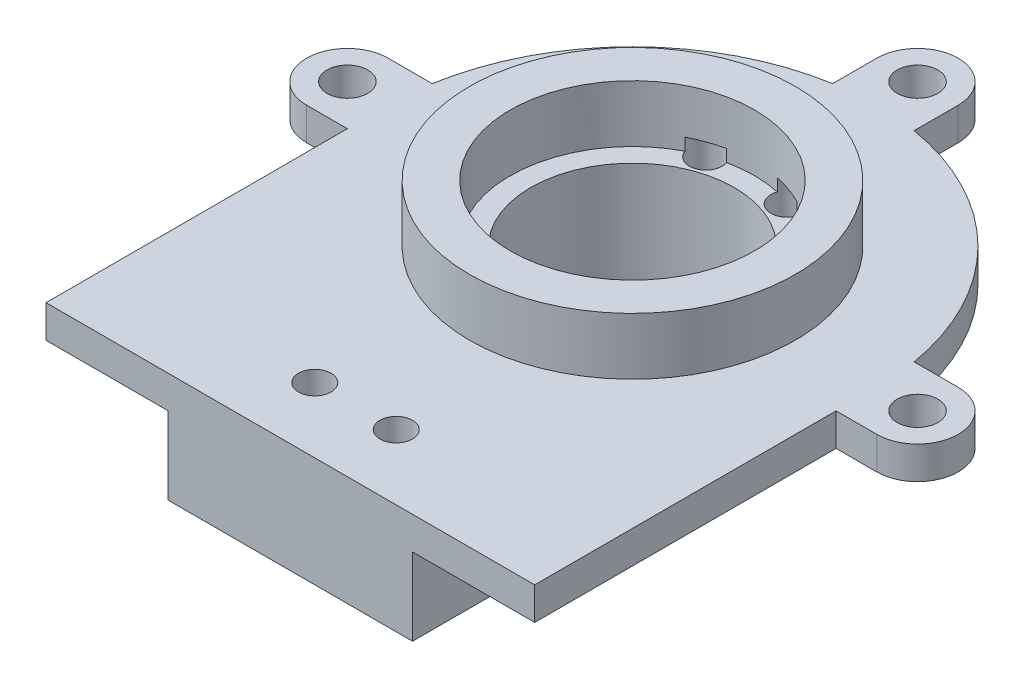
SolidWorks part; units mm, degrees
ref_plane "Спереди" through (0, 0, 0) normal (0, 0, 1) x (1, 0, 0)
ref_plane "Сверху" through (0, 0, 0) normal (0, 1, 0) x (1, 0, 0)
ref_plane "Справа" through (0, 0, 0) normal (1, 0, 0) x (0, 0, -1)
sketch "Эскиз1" plane through (0, 0, 0) normal (0, 1, 0) x (1, 0, 0)
  circle A0 centre (0, 0) radius 20
  circle A1 centre (0, 0) radius 15
  dimension "D1" = 40
  dimension "D2" = 30
extrude "Бобышка-Вытянуть1" add sketch "Эскиз1" along normal blind 7
sketch "Эскиз2" plane through (0, 0, 0) normal (0, -1, 0) x (1, 0, 0)
  circle A0 centre (0, 0) radius 70
  circle A1 centre (0, 0) radius 12.5
  dimension "D1" = 140
  dimension "D2" = 25
extrude "Бобышка-Вытянуть2" add sketch "Эскиз2" along normal blind 4
sketch "Эскиз3" plane through (0, -4, 0) normal (0, -1, 0) x (1, 0, 0)
  line L0 (10, -6.7) -> (10, 26.7) construction
  line L1 (15, -22) -> (-15, -22)
  line L2 (15, -22) -> (15, 42)
  line L3 (15, 42) -> (-15, 42)
  line L4 (-15, -22) -> (-15, 42)
  line L5 (-10, 26.7) -> (-10, -6.7) construction
  line L6 (-3.6083, -17) -> (3.6083, -17) construction
  line L7 (3.6083, 37) -> (-3.6083, 37) construction
  circle A0 centre (-5, 34) radius 2
  circle A1 centre (5, 34) radius 2
  circle A2 centre (-5, -14) radius 2
  circle A3 centre (5, -14) radius 2
  circle A4 centre (0, 0) radius 12.5
  dimension "D5" = 25
  dimension "D1" = 5
  dimension "D2" = 5
  dimension "D3" = 5
  dimension "D4" = 5
extrude "Бобышка-Вытянуть3" add sketch "Эскиз3" along normal blind 9.5
sketch "Эскиз4" plane through (0, 0, 0) normal (0, 1, 0) x (1, 0, 0)
  line L0 (-1000, 0) -> (49000, 0) construction
  line L1 (-30, 0) -> (-30, -42)
  line L2 (-30, -42) -> (30, -42)
  line L3 (30, -42) -> (30, 0)
  arc A0 (30, 0) -> (-30, 0) centre (0, 0) ccw
  circle A1 centre (0, 0) radius 81.1685
  dimension "D1" = 60
  dimension "D2" = 60
  dimension "D3" = 42
extrude "Вырез-Вытянуть1" cut sketch "Эскиз4" against normal blind 9.5
sketch "Эскиз6" plane through (0, -13.5, 0) normal (0, -1, 0) x (1, 0, 0)
  circle A0 centre (-5, 34) radius 2
  circle A1 centre (5, 34) radius 2
  circle A2 centre (-5, -14) radius 2
  circle A3 centre (5, -14) radius 2
extrude "Вырез-Вытянуть2" cut sketch "Эскиз6" against normal blind 15
sketch "Эскиз7" plane through (0, 0, 0) normal (0, 1, 0) x (1, 0, 0)
  line L0 (-1000, 0) -> (49000, 0) construction
  line L1 (0, -1000) -> (0, 49000) construction
  line L2 (-35, 5) -> (-27, 5)
  line L3 (-27, 5) -> (-27, -5)
  line L4 (-27, -5) -> (-35, -5)
  line L5 (-5, 35) -> (-5, 27)
  line L6 (-5, 27) -> (5, 27)
  line L7 (5, 27) -> (5, 35)
  line L8 (35, 5) -> (27, 5)
  line L9 (27, 5) -> (27, -5)
  line L10 (27, -5) -> (35, -5)
  circle A0 centre (-35, 0) radius 2.5
  circle A1 centre (35, 0) radius 2.5
  circle A2 centre (0, 35) radius 2.5
  arc A3 (-35, 5) -> (-35, -5) centre (-35, 0) ccw
  arc A5 (5, 35) -> (-5, 35) centre (0, 35) ccw
  arc A6 (35, -5) -> (35, 5) centre (35, 0) ccw
  dimension "D1" = 5
  dimension "D3" = 5
  dimension "D5" = 5
  dimension "D7" = 10
  dimension "D8" = 10
  dimension "D2" = 35
  dimension "D4" = 70
  dimension "D6" = 35
  dimension "D9" = 8
  dimension "D10" = 8
  dimension "D11" = 8
  dimension "D12" = 10
  dimension "D13" = 10
  dimension "D14" = 8
extrude "Бобышка-Вытянуть4" add sketch "Эскиз7" against normal blind 4
